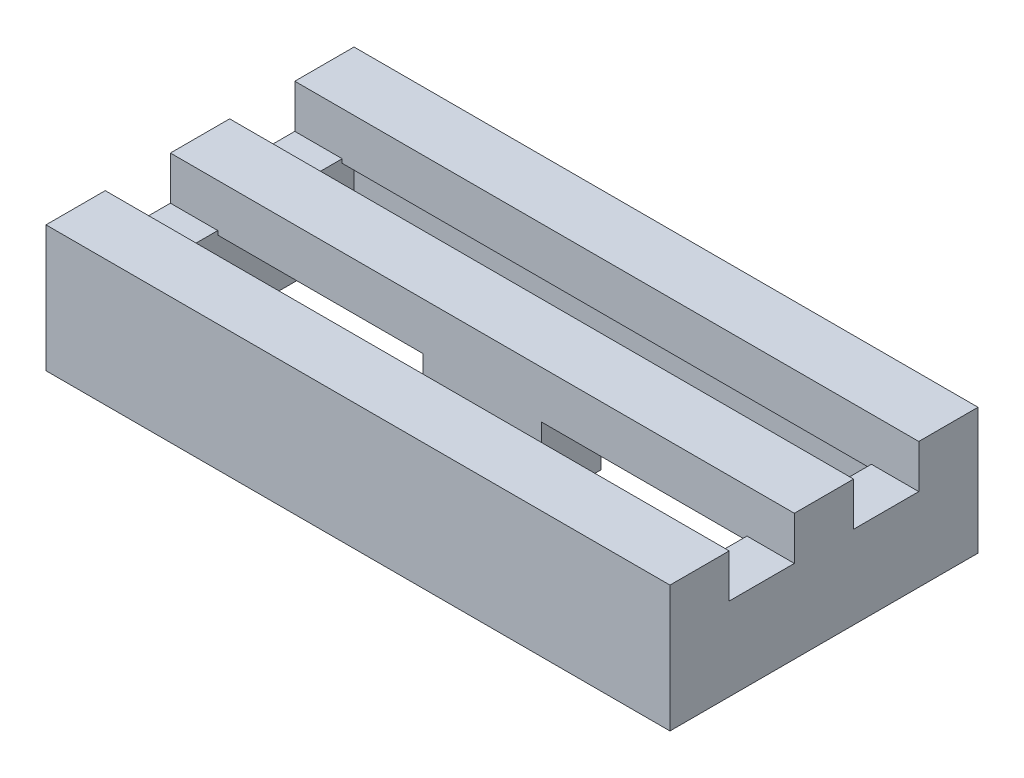
SolidWorks part; units mm, degrees
material "ABS"
ref_plane "Front Plane" through (0, 0, 0) normal (0, 0, 1) x (1, 0, 0)
ref_plane "Top Plane" through (0, 0, 0) normal (0, 1, 0) x (1, 0, 0)
ref_plane "Right Plane" through (0, 0, 0) normal (1, 0, 0) x (0, 0, -1)
sketch "Sketch1" plane through (0, 0, 0) normal (0, 0, 1) x (1, 0, 0)
  line L1 (0, 0) -> (15.8, 0)
  line L2 (0, 0) -> (0, 3.2)
  line L3 (0, 3.2) -> (15.8, 3.2)
  line L4 (15.8, 0) -> (15.8, 3.2)
  dimension "D1" = 3.2
  dimension "D2" = 15.8
extrude "Boss-Extrude1" add sketch "Sketch1" against normal blind 7.8
shell "Shell1" thickness 1.2
sketch "Sketch3" plane through (0, 3.2, 0) normal (0, 1, 0) x (1, 0, 0)
  line L0 (0, 7.8) -> (0, 6.3) construction
  line L1 (0, 7.8) -> (15.8, 7.8) construction
  line L2 (15.8, 7.8) -> (15.8, 0) construction
  line L3 (15.8, 0) -> (0, 0) construction
  line L4 (0, 7.8) -> (0, 0) construction
  line L5 (0, 6.3) -> (15.8, 6.3)
  line L6 (0, 6.3) -> (0, 4.65)
  line L7 (0, 4.65) -> (15.8, 4.65)
  line L8 (15.8, 4.65) -> (15.8, 6.3)
  dimension "D1" = 1.5
  dimension "D2" = 1.65
extrude "Cut-Extrude1" cut sketch "Sketch3" against normal blind 1.1
pattern_linear "LPattern1" count 2 spacing 3.15 along (0, 0, 1) of "Cut-Extrude1"
sketch "Sketch5" plane through (0, 2.1, 0) normal (0, 1, 0) x (1, 0, 0)
  line L0 (0, 4.65) -> (1.2, 4.65) construction
  line L1 (0, 4.65) -> (15.8, 4.65) construction
  line L2 (15.8, 4.65) -> (14.6, 4.65) construction
  line L3 (0, 4.65) -> (15.8, 4.65) construction
  line L4 (1.2, 4.65) -> (1.2, 6.3)
  line L5 (15.8, 6.3) -> (0, 6.3) construction
  line L6 (1.2, 4.65) -> (14.6, 4.65)
  line L7 (14.6, 4.65) -> (14.6, 6.3)
  line L8 (15.8, 6.3) -> (0, 6.3) construction
  line L9 (14.6, 6.3) -> (1.2, 6.3)
  dimension "D1" = 1.2
  dimension "D2" = 1.2
extrude "Cut-Extrude2" cut sketch "Sketch5" against normal through all
pattern_linear "LPattern2" count 2 spacing 3.15 along (0, 0, 1) of "Cut-Extrude2"
sketch "Sketch7" plane through (0, 2, 0) normal (0, -1, 0) x (1, 0, 0)
  line L0 (1.2, -3.15) -> (14.6, -3.15) construction
  line L1 (7.9, -3.15) -> (7.9, -4.65) construction
  line L2 (1.2, -4.65) -> (14.6, -4.65) construction
  line L3 (6.4, -3.15) -> (9.4, -3.15)
  line L4 (6.4, -3.15) -> (6.4, -4.65)
  line L5 (6.4, -4.65) -> (9.4, -4.65)
  line L6 (9.4, -4.65) -> (9.4, -3.15)
  point P11 (7.9, -3.15)
  dimension "D1" = 3
extrude "Boss-Extrude2" add sketch "Sketch7" along normal offset from surface (1.8 mm away) 0.2 up to face at (7.9, 0, -3.9)
